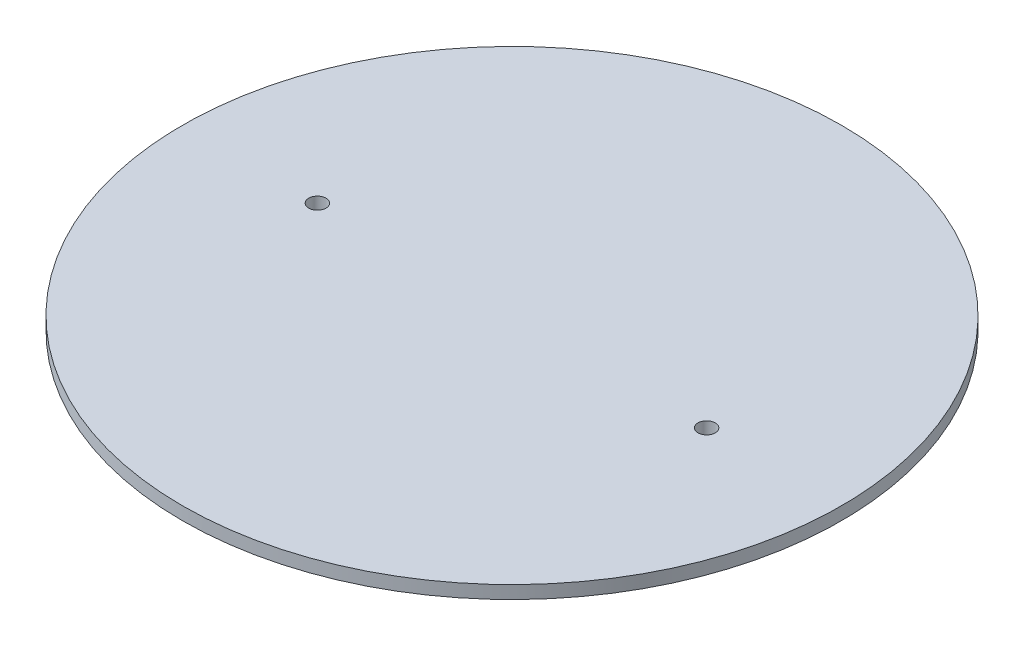
SolidWorks part; units mm, degrees
material "1060 Alloy"
ref_plane "Front Plane" through (0, 0, 0) normal (0, 0, 1) x (1, 0, 0)
ref_plane "Top Plane" through (0, 0, 0) normal (0, 1, 0) x (1, 0, 0)
ref_plane "Right Plane" through (0, 0, 0) normal (1, 0, 0) x (0, 0, -1)
sketch "Sketch1" plane through (0, 0, 0) normal (0, 1, 0) x (1, 0, 0)
  line L0 (76.2, 0) -> (-76.2, 0) construction
  circle A0 centre (0, 0) radius 76.2
  circle A1 centre (45, 0) radius 2
  circle A2 centre (-45, 0) radius 2
  point P9 (0, 0)
  dimension "D1" = 152.4
  dimension "D2" = 4
  dimension "D3" = 4
  dimension "D4" = 90
  dimension "D5" = 45
extrude "Boss-Extrude1" add sketch "Sketch1" along normal blind 3
